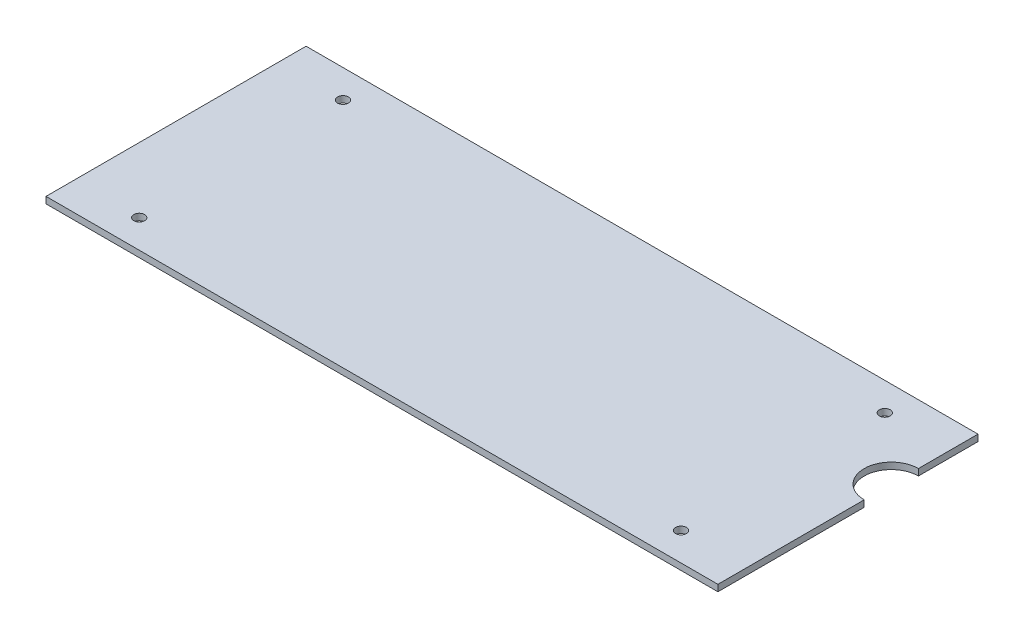
SolidWorks part; units mm, degrees
ref_plane "Front Plane" through (0, 0, 0) normal (0, 0, 1) x (1, 0, 0)
ref_plane "Top Plane" through (0, 0, 0) normal (0, 1, 0) x (1, 0, 0)
ref_plane "Right Plane" through (0, 0, 0) normal (1, 0, 0) x (0, 0, -1)
sketch "Sketch1" plane through (0, 0, 0) normal (0, 1, 0) x (1, 0, 0)
  line L0 (0, 74.7612) -> (0, -88.7735) construction
  line L1 (-155, -60) -> (155, -60)
  line L2 (-155, -60) -> (-155, 60)
  line L3 (-155, 60) -> (155, 60)
  line L4 (155, -60) -> (155, 60)
  line L5 (-155, -60) -> (155, 60) construction
  line L6 (-155, 60) -> (155, -60) construction
  line L7 (-193.2666, 0) -> (173.7014, 0) construction
  circle A0 centre (-125, 47) radius 2.5
  circle A1 centre (125, 47) radius 2.5
  circle A2 centre (125, -47) radius 2.5
  circle A3 centre (-125, -47) radius 2.5
  point P0 (0, 0)
  dimension "D3" = 5
  dimension "D4" = 13
  dimension "D5" = 30
  dimension "D1" = 310
  dimension "D2" = 120
extrude "Boss-Extrude1" add sketch "Sketch1" along normal blind 3
sketch "Sketch2" plane through (0, 0, 0) normal (0, -1, 0) x (1, 0, 0)
  line L0 (155, 60) -> (155, -60) construction
  line L1 (155, -60) -> (-155, -60) construction
  circle A0 centre (155, -20) radius 12.5
  dimension "D2" = 25
  dimension "D1" = 40
extrude "Cut-Extrude1" cut sketch "Sketch2" against normal up to next
